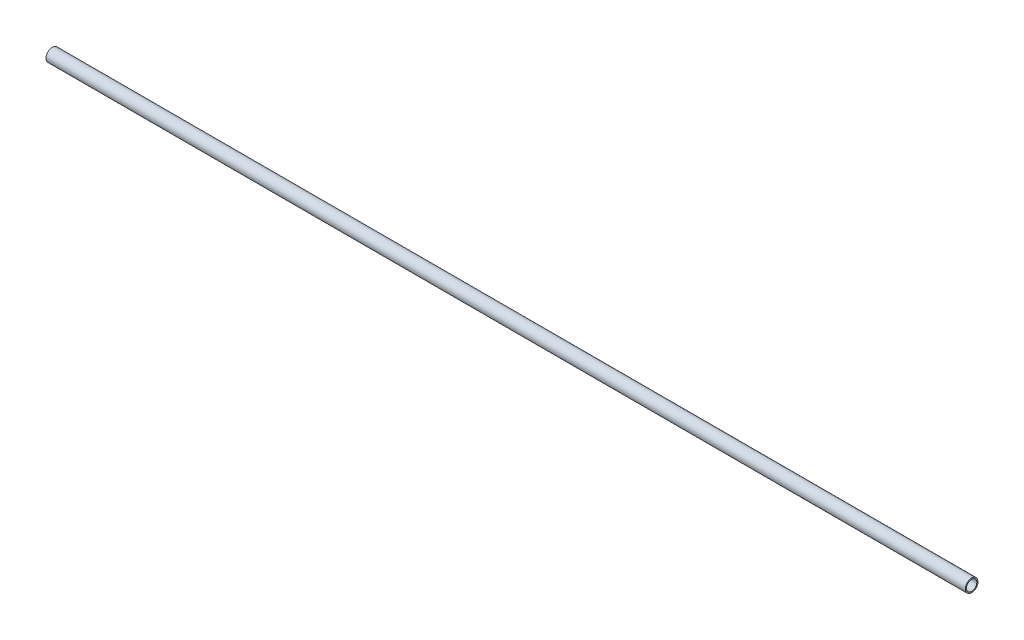
SolidWorks part; units mm, degrees
material "AISI 4130 Steel, annealed at 865C"
ref_plane "Front Plane" through (0, 0, 0) normal (0, 0, 1) x (1, 0, 0)
ref_plane "Top Plane" through (0, 0, 0) normal (0, 1, 0) x (1, 0, 0)
ref_plane "Right Plane" through (0, 0, 0) normal (1, 0, 0) x (0, 0, -1)
sketch "Sketch1" plane through (0, 0, 0) normal (1, 0, 0) x (0, 0, -1)
  circle A0 centre (0, 0) radius 12.7
  circle A1 centre (0, 0) radius 10.287
  dimension "D1" = 25.4
  dimension "D2" = 2.413
extrude "Boss-Extrude1" add sketch "Sketch1" along normal blind 1828.8
